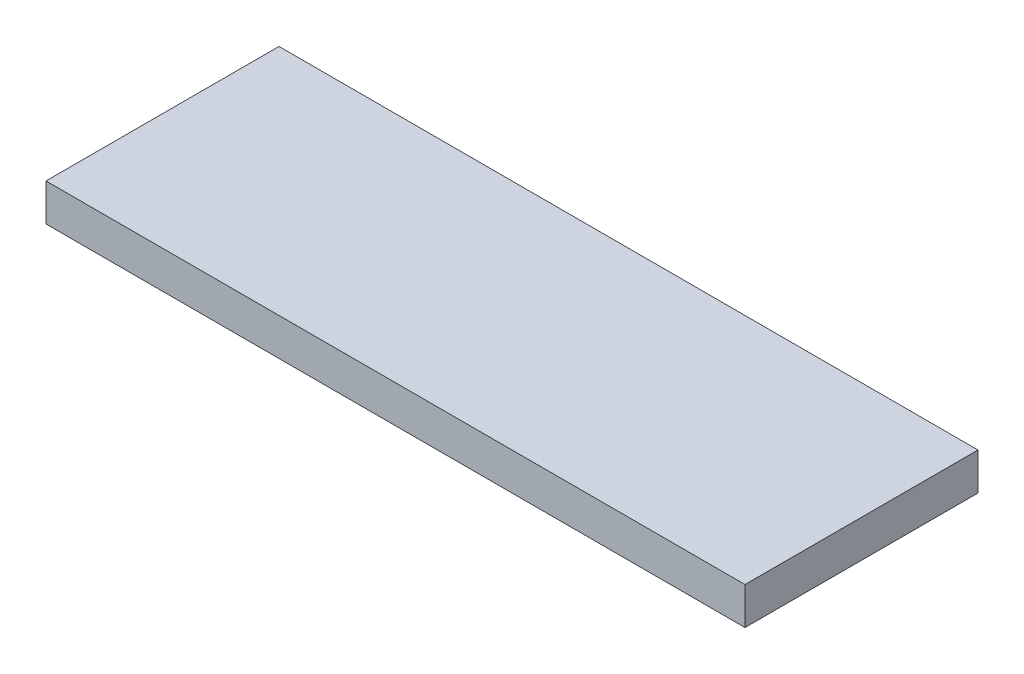
SolidWorks part; units mm, degrees
ref_plane "Front Plane" through (0, 0, 0) normal (0, 0, 1) x (1, 0, 0)
ref_plane "Top Plane" through (0, 0, 0) normal (0, 1, 0) x (1, 0, 0)
ref_plane "Right Plane" through (0, 0, 0) normal (1, 0, 0) x (0, 0, -1)
sketch "Sketch1" plane through (0, 0, 0) normal (0, 1, 0) x (1, 0, 0)
  line L1 (-750, 250) -> (750, 250)
  line L2 (-750, 250) -> (-750, -250)
  line L3 (-750, -250) -> (750, -250)
  line L4 (750, 250) -> (750, -250)
  line L5 (-750, 250) -> (750, -250) construction
  line L6 (-750, -250) -> (750, 250) construction
  point P0 (0, 0)
  dimension "D1" = 1500
  dimension "D2" = 500
extrude "Boss-Extrude1" add sketch "Sketch1" along normal blind 80
